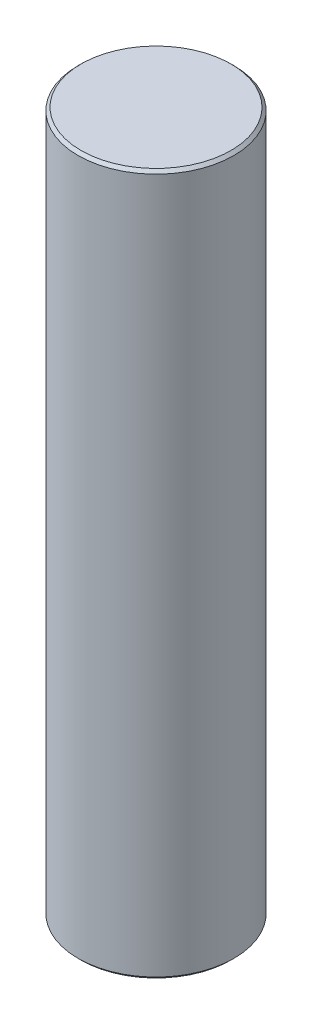
SolidWorks part; units mm, degrees
material "Ductile Iron (SN)"
ref_plane "Front Plane" through (0, 0, 0) normal (0, 0, 1) x (1, 0, 0)
ref_plane "Top Plane" through (0, 0, 0) normal (0, 1, 0) x (1, 0, 0)
ref_plane "Right Plane" through (0, 0, 0) normal (1, 0, 0) x (0, 0, -1)
sketch "Sketch1" plane through (0, 0, 0) normal (0, 1, 0) x (1, 0, 0)
  circle A0 centre (0, 0) radius 4
  dimension "D1" = 8
extrude "Boss-Extrude1" add sketch "Sketch1" along normal blind 36
chamfer "Chamfer1" distance 0.15 angle 45 2 edges at (0, 0, 4) (0, 36, 4)
